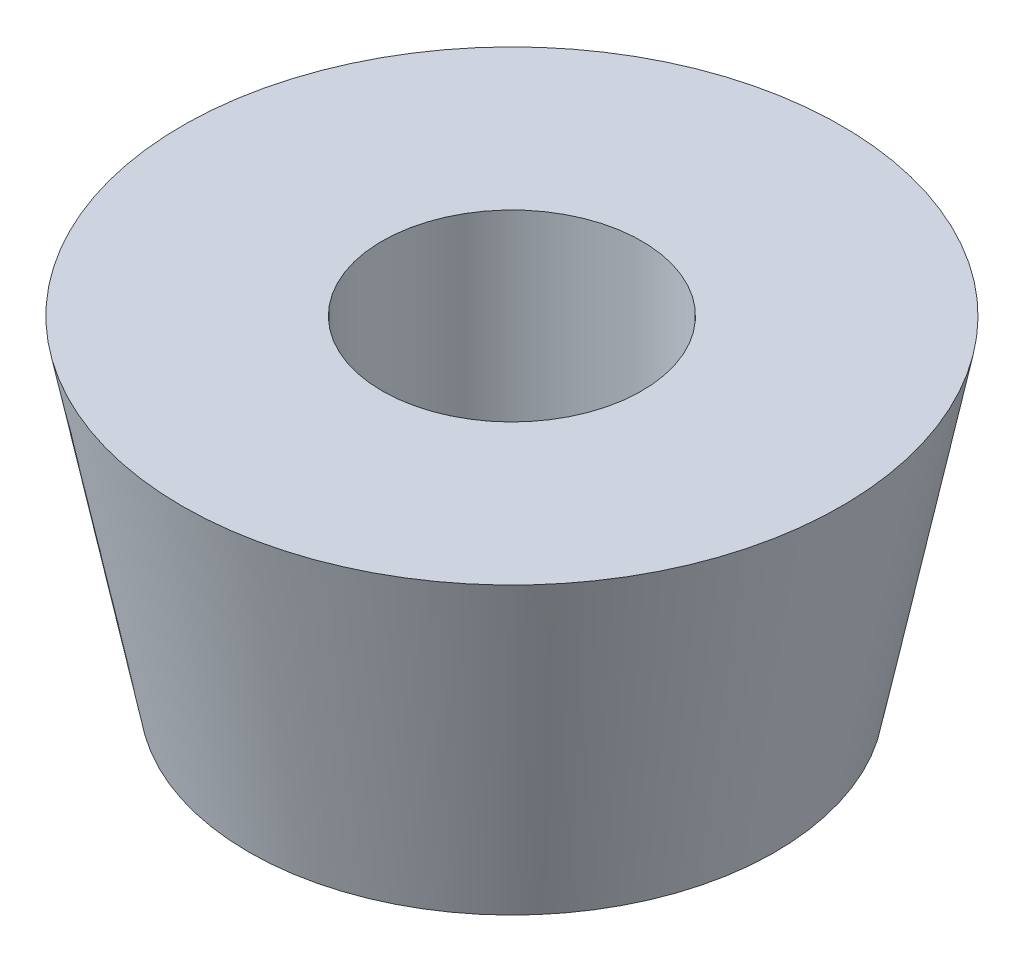
SolidWorks part; units mm, degrees
ref_plane "Front Plane" through (0, 0, 0) normal (0, 0, 1) x (1, 0, 0)
ref_plane "Top Plane" through (0, 0, 0) normal (0, 1, 0) x (1, 0, 0)
ref_plane "Right Plane" through (0, 0, 0) normal (1, 0, 0) x (0, 0, -1)
sketch "Sketch1" plane through (0, 0, 0) normal (0, 0, 1) x (1, 0, 0)
  line L0 (0, 0) -> (0, -5) construction
  line L1 (1.95, 0) -> (1.95, -5)
  line L2 (1.95, -5) -> (3.95, -5)
  line L3 (3.95, -5) -> (4.95, 0)
  line L4 (4.95, 0) -> (1.95, 0)
  point P5 (0, 0)
  point P8 (0, 0)
  point P9 (-5.7755, 0.6313)
  point P10 (3.95, -5)
  point P11 (4.95, 0)
  dimension "D1" = 5
  dimension "D2" = 3.9
  dimension "D3" = 3
  dimension "D4" = 2
revolve "Revolve1" add sketch "Sketch1" angle 360 about L0
